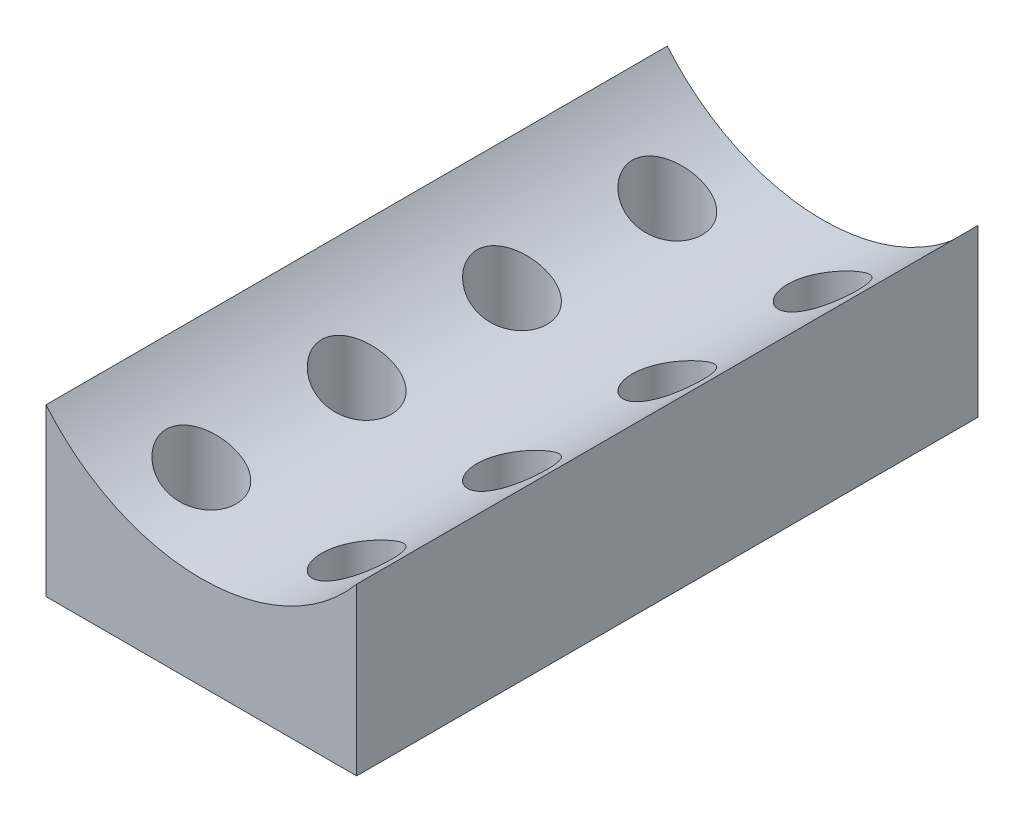
SolidWorks part; units mm, degrees
ref_plane "Front Plane" through (0, 0, 0) normal (0, 0, 1) x (1, 0, 0)
ref_plane "Top Plane" through (0, 0, 0) normal (0, 1, 0) x (1, 0, 0)
ref_plane "Right Plane" through (0, 0, 0) normal (1, 0, 0) x (0, 0, -1)
sketch "Sketch1" plane through (0, 0, 0) normal (0, 0, 1) x (1, 0, 0)
  line L1 (-10, -5.3467) -> (10, -5.3467)
  line L2 (-10, -5.3467) -> (-10, 5.3467)
  line L3 (-10, 5.3467) -> (10, 5.3467) construction
  line L4 (10, -5.3467) -> (10, 5.3467)
  line L5 (-10, -5.3467) -> (10, 5.3467) construction
  line L6 (-10, 5.3467) -> (10, -5.3467) construction
  arc A0 (-10, 5.3467) -> (10, 5.3467) centre (0, 13.6533) ccw
  point P0 (0, 0)
  dimension "D3" = 26
  dimension "D1" = 20
  dimension "D2" = 19
extrude "Boss-Extrude1" add sketch "Sketch1" along normal blind 40
sketch "Sketch2" plane through (0, -5.3467, 0) normal (0, -1, 0) x (1, 0, 0)
  line L0 (-5, 5) -> (5, 5) construction
  line L1 (0, 5) -> (0, 0) construction
  circle A0 centre (5, 5) radius 2.25
  circle A1 centre (-5, 5) radius 2.25
  circle A2 centre (-5, 15) radius 2.25
  circle A3 centre (5, 15) radius 2.25
  circle A4 centre (-5, 25) radius 2.25
  circle A5 centre (5, 25) radius 2.25
  circle A6 centre (-5, 35) radius 2.25
  circle A7 centre (5, 35) radius 2.25
  dimension "D2" = 4.5
  dimension "D1" = 10
  dimension "D3" = 5
  dimension "D5" = 10
  dimension "D4" = 4
extrude "Cut-Extrude1" cut sketch "Sketch2" against normal through all
chamfer "Chamfer1" distance 1 angle 45 8 edges at (-5, -5.3467, 32.75) (5, -5.3467, 32.75) (5, -5.3467, 22.75) (-5, -5.3467, 22.75) (-5, -5.3467, 12.75) (5, -5.3467, 12.75) (5, -5.3467, 2.75) (-5, -5.3467, 2.75)
